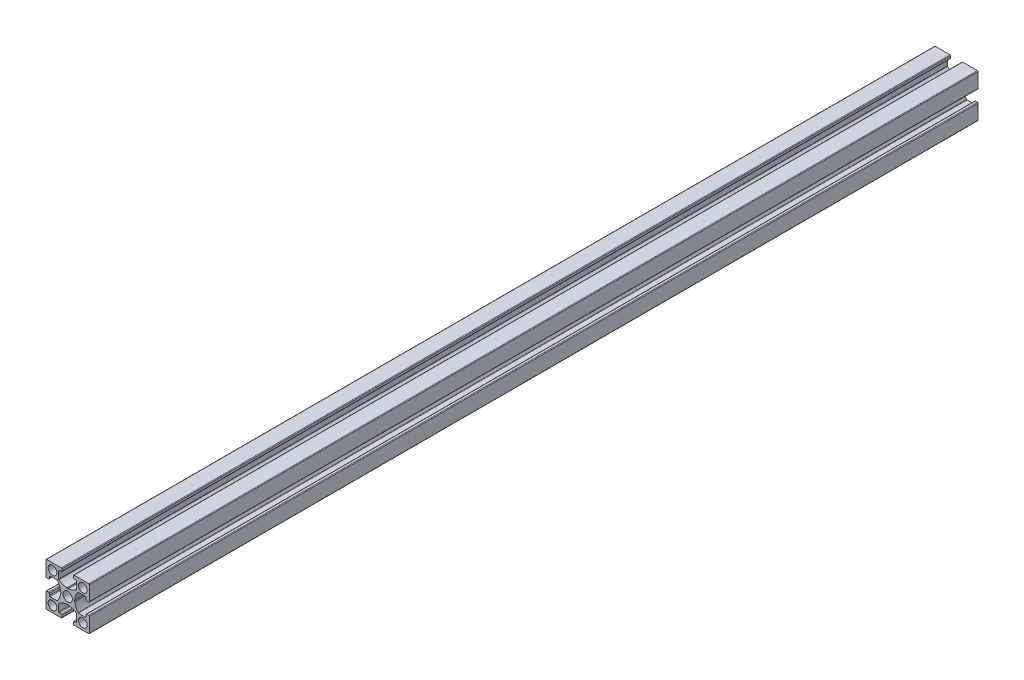
SolidWorks part; units mm, degrees
ref_plane "정면" through (0, 0, 0) normal (0, 0, 1) x (1, 0, 0)
ref_plane "윗면" through (0, 0, 0) normal (0, 1, 0) x (1, 0, 0)
ref_plane "우측면" through (0, 0, 0) normal (1, 0, 0) x (0, 0, -1)
sketch "Model" plane through (0, 0, 0) normal (0, 0, 1) x (1, 0, 0)
  line L0 (2292.4151, 1187.1915) -> (2314.8128, 1187.1915) construction
  line L1 (2307.7639, 1192.1343) -> (2307.7639, 1195.3915)
  line L2 (2307.4639, 1195.6915) -> (2306.5639, 1195.6915)
  line L3 (2306.2639, 1195.9915) -> (2306.2639, 1196.8915)
  line L4 (2306.5639, 1197.1915) -> (2313.3139, 1197.1915)
  line L5 (2313.6139, 1196.8915) -> (2313.6139, 1190.1415)
  line L6 (2313.3139, 1189.8415) -> (2312.4139, 1189.8415)
  line L7 (2312.1139, 1190.1415) -> (2312.1139, 1191.0415)
  line L8 (2311.8139, 1191.3415) -> (2308.5567, 1191.3415)
  line L9 (2306.9212, 1187.4988) -> (2306.6139, 1187.1915)
  line L10 (2306.6139, 1187.1915) -> (2306.9212, 1186.8843)
  line L11 (2308.5567, 1183.0415) -> (2311.8139, 1183.0415)
  line L12 (2312.1139, 1183.3415) -> (2312.1139, 1184.2415)
  line L13 (2312.4139, 1184.5415) -> (2313.3139, 1184.5415)
  line L14 (2313.6139, 1184.2415) -> (2313.6139, 1177.4915)
  line L15 (2313.3139, 1177.1915) -> (2306.5639, 1177.1915)
  line L16 (2306.2639, 1177.4915) -> (2306.2639, 1178.3915)
  line L17 (2306.5639, 1178.6915) -> (2307.4639, 1178.6915)
  line L18 (2307.7639, 1178.9915) -> (2307.7639, 1182.2488)
  line L19 (2303.9212, 1183.8843) -> (2303.6139, 1184.1915)
  line L20 (2303.6139, 1184.1915) -> (2303.3066, 1183.8843)
  line L21 (2299.4639, 1182.2488) -> (2299.4639, 1178.9915)
  line L22 (2299.7639, 1178.6915) -> (2300.6639, 1178.6915)
  line L23 (2300.9639, 1178.3915) -> (2300.9639, 1177.4915)
  line L24 (2300.6639, 1177.1915) -> (2293.9139, 1177.1915)
  line L25 (2293.6139, 1177.4915) -> (2293.6139, 1184.2415)
  line L26 (2293.9139, 1184.5415) -> (2294.8139, 1184.5415)
  line L27 (2295.1139, 1184.2415) -> (2295.1139, 1183.3415)
  line L28 (2295.4139, 1183.0415) -> (2298.6712, 1183.0415)
  line L29 (2300.3066, 1186.8843) -> (2300.6139, 1187.1915)
  line L30 (2300.6139, 1187.1915) -> (2300.3066, 1187.4988)
  line L31 (2298.6712, 1191.3415) -> (2295.4139, 1191.3415)
  line L32 (2295.1139, 1191.0415) -> (2295.1139, 1190.1415)
  line L33 (2294.8139, 1189.8415) -> (2293.9139, 1189.8415)
  line L34 (2293.6139, 1190.1415) -> (2293.6139, 1196.8915)
  line L35 (2293.9139, 1197.1915) -> (2300.6639, 1197.1915)
  line L36 (2300.9639, 1196.8915) -> (2300.9639, 1195.9915)
  line L37 (2300.6639, 1195.6915) -> (2299.7639, 1195.6915)
  line L38 (2299.4639, 1195.3915) -> (2299.4639, 1192.1343)
  line L39 (2303.3066, 1190.4988) -> (2303.6139, 1190.1915)
  line L40 (2303.6139, 1190.1915) -> (2303.9212, 1190.4988)
  line L41 (2294.1139, 1194.1915) -> (2299.1139, 1194.1915) construction
  line L42 (2296.6139, 1196.6915) -> (2296.6139, 1191.6915) construction
  line L43 (2294.1139, 1180.1915) -> (2299.1139, 1180.1915) construction
  line L44 (2296.6139, 1177.6915) -> (2296.6139, 1182.6915) construction
  line L45 (2303.6139, 1198.3904) -> (2303.6139, 1175.9927) construction
  line L46 (2313.1139, 1194.1915) -> (2308.1139, 1194.1915) construction
  line L47 (2310.6139, 1196.6915) -> (2310.6139, 1191.6915) construction
  line L48 (2310.6139, 1177.6915) -> (2310.6139, 1182.6915) construction
  line L49 (2313.1139, 1180.1915) -> (2308.1139, 1180.1915) construction
  circle A0 centre (2303.6139, 1187.1915) radius 2.15
  circle A1 centre (2296.6139, 1194.1915) radius 2
  circle A2 centre (2296.6139, 1180.1915) radius 2
  circle A3 centre (2310.6139, 1194.1915) radius 2
  circle A4 centre (2310.6139, 1180.1915) radius 2
  arc A5 (2307.7639, 1195.3915) -> (2307.4639, 1195.6915) centre (2307.4639, 1195.3915) ccw
  arc A6 (2306.2639, 1195.9915) -> (2306.5639, 1195.6915) centre (2306.5639, 1195.9915) ccw
  arc A7 (2306.5639, 1197.1915) -> (2306.2639, 1196.8915) centre (2306.5639, 1196.8915) ccw
  arc A8 (2313.6139, 1196.8915) -> (2313.3139, 1197.1915) centre (2313.3139, 1196.8915) ccw
  arc A9 (2313.3139, 1189.8415) -> (2313.6139, 1190.1415) centre (2313.3139, 1190.1415) ccw
  arc A10 (2312.1139, 1190.1415) -> (2312.4139, 1189.8415) centre (2312.4139, 1190.1415) ccw
  arc A11 (2312.1139, 1191.0415) -> (2311.8139, 1191.3415) centre (2311.8139, 1191.0415) ccw
  arc A12 (2308.5567, 1191.3415) -> (2308.3217, 1191.2281) centre (2308.5567, 1191.0415) ccw
  arc A13 (2308.3217, 1191.2281) -> (2306.9212, 1187.4988) centre (2313.4048, 1187.1915) ccw
  arc A14 (2306.9212, 1186.8843) -> (2308.3217, 1183.155) centre (2313.4048, 1187.1915) ccw
  arc A15 (2308.3217, 1183.155) -> (2308.5567, 1183.0415) centre (2308.5567, 1183.3415) ccw
  arc A16 (2311.8139, 1183.0415) -> (2312.1139, 1183.3415) centre (2311.8139, 1183.3415) ccw
  arc A17 (2312.4139, 1184.5415) -> (2312.1139, 1184.2415) centre (2312.4139, 1184.2415) ccw
  arc A18 (2313.6139, 1184.2415) -> (2313.3139, 1184.5415) centre (2313.3139, 1184.2415) ccw
  arc A19 (2313.3139, 1177.1915) -> (2313.6139, 1177.4915) centre (2313.3139, 1177.4915) ccw
  arc A20 (2306.2639, 1177.4915) -> (2306.5639, 1177.1915) centre (2306.5639, 1177.4915) ccw
  arc A21 (2306.5639, 1178.6915) -> (2306.2639, 1178.3915) centre (2306.5639, 1178.3915) ccw
  arc A22 (2307.4639, 1178.6915) -> (2307.7639, 1178.9915) centre (2307.4639, 1178.9915) ccw
  arc A23 (2307.7639, 1182.2488) -> (2307.6505, 1182.4837) centre (2307.4639, 1182.2488) ccw
  arc A24 (2307.6505, 1182.4837) -> (2303.9212, 1183.8843) centre (2303.6139, 1177.4007) ccw
  arc A25 (2303.3066, 1183.8843) -> (2299.5774, 1182.4837) centre (2303.6139, 1177.4007) ccw
  arc A26 (2299.5774, 1182.4837) -> (2299.4639, 1182.2488) centre (2299.7639, 1182.2488) ccw
  arc A27 (2299.4639, 1178.9915) -> (2299.7639, 1178.6915) centre (2299.7639, 1178.9915) ccw
  arc A28 (2300.9639, 1178.3915) -> (2300.6639, 1178.6915) centre (2300.6639, 1178.3915) ccw
  arc A29 (2300.6639, 1177.1915) -> (2300.9639, 1177.4915) centre (2300.6639, 1177.4915) ccw
  arc A30 (2293.6139, 1177.4915) -> (2293.9139, 1177.1915) centre (2293.9139, 1177.4915) ccw
  arc A31 (2293.9139, 1184.5415) -> (2293.6139, 1184.2415) centre (2293.9139, 1184.2415) ccw
  arc A32 (2295.1139, 1184.2415) -> (2294.8139, 1184.5415) centre (2294.8139, 1184.2415) ccw
  arc A33 (2295.1139, 1183.3415) -> (2295.4139, 1183.0415) centre (2295.4139, 1183.3415) ccw
  arc A34 (2298.6712, 1183.0415) -> (2298.9061, 1183.155) centre (2298.6712, 1183.3415) ccw
  arc A35 (2298.9061, 1183.155) -> (2300.3066, 1186.8843) centre (2293.8231, 1187.1915) ccw
  arc A36 (2300.3066, 1187.4988) -> (2298.9061, 1191.2281) centre (2293.8231, 1187.1915) ccw
  arc A37 (2298.9061, 1191.2281) -> (2298.6712, 1191.3415) centre (2298.6712, 1191.0415) ccw
  arc A38 (2295.4139, 1191.3415) -> (2295.1139, 1191.0415) centre (2295.4139, 1191.0415) ccw
  arc A39 (2294.8139, 1189.8415) -> (2295.1139, 1190.1415) centre (2294.8139, 1190.1415) ccw
  arc A40 (2293.6139, 1190.1415) -> (2293.9139, 1189.8415) centre (2293.9139, 1190.1415) ccw
  arc A41 (2293.9139, 1197.1915) -> (2293.6139, 1196.8915) centre (2293.9139, 1196.8915) ccw
  arc A42 (2300.9639, 1196.8915) -> (2300.6639, 1197.1915) centre (2300.6639, 1196.8915) ccw
  arc A43 (2300.6639, 1195.6915) -> (2300.9639, 1195.9915) centre (2300.6639, 1195.9915) ccw
  arc A44 (2299.7639, 1195.6915) -> (2299.4639, 1195.3915) centre (2299.7639, 1195.3915) ccw
  arc A45 (2299.4639, 1192.1343) -> (2299.5774, 1191.8994) centre (2299.7639, 1192.1343) ccw
  arc A46 (2299.5774, 1191.8994) -> (2303.3066, 1190.4988) centre (2303.6139, 1196.9824) ccw
  arc A47 (2303.9212, 1190.4988) -> (2307.6505, 1191.8994) centre (2303.6139, 1196.9824) ccw
  arc A48 (2307.6505, 1191.8994) -> (2307.7639, 1192.1343) centre (2307.4639, 1192.1343) ccw
extrude "보스-돌출1" add sketch "Model" along normal blind 410
